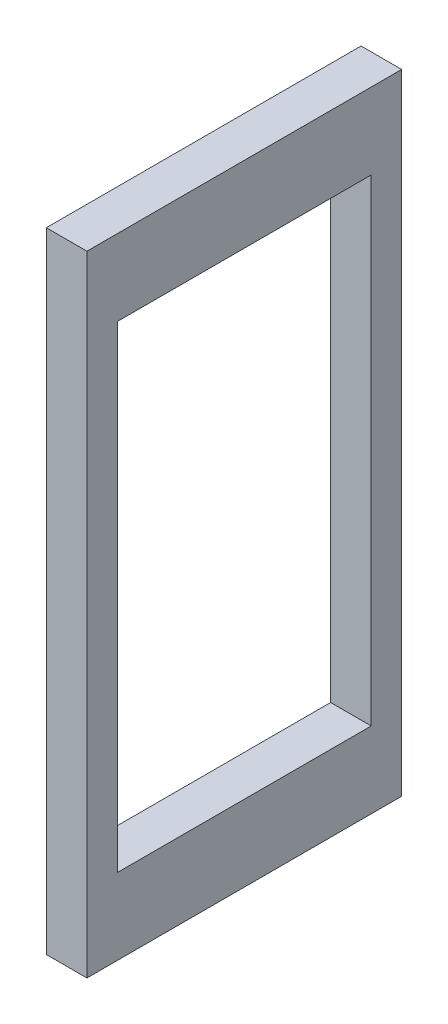
SolidWorks part; units mm, degrees
ref_plane "Front Plane" through (0, 0, 0) normal (1, 0, 0) x (0, 1, 0)
ref_plane "Top Plane" through (0, 0, 0) normal (0, 0, 1) x (0, 1, 0)
ref_plane "Right Plane" through (0, 0, 0) normal (0, 1, 0) x (-1, 0, 0)
sketch "Sketch1" plane through (0, 0, 0) normal (1, 0, 0) x (0, 1, 0)
  line L0 (-15.1573, 5.6511) -> (-15.1573, 7.1511)
  line L1 (12.0919, -6.8489) -> (-11.4081, -6.8489)
  line L2 (15.8412, -7.1519) -> (15.8412, 6.8481)
  line L3 (12.0919, 5.6511) -> (-11.4081, 5.6511)
  line L4 (-15.1573, -6.8489) -> (-15.1573, 5.6511)
  line L7 (12.0919, -6.8489) -> (-11.4081, -6.8489)
  line L8 (12.0919, -6.8489) -> (12.0919, 5.6511)
  line L9 (12.0919, 5.6511) -> (-11.4081, 5.6511)
  line L10 (-11.4081, -6.8489) -> (-11.4081, 5.6511)
  line L13 (-11.4081, 5.6511) -> (12.0919, 5.6511)
  line L14 (-15.1573, 7.1511) -> (15.8412, 7.1511)
  line L15 (15.8412, 6.8481) -> (15.8412, 7.1511)
  line L16 (-15.1573, -6.8489) -> (-15.1573, -8.3489)
  line L17 (-11.4081, -6.8489) -> (12.0919, -6.8489)
  line L18 (-15.1573, -8.3489) -> (15.8412, -8.3489)
  line L19 (15.8412, -7.1519) -> (15.8412, -8.3489)
  point P0 (0, 0)
  point P6 (0.3419, -0.1511)
  point P11 (0, 0)
  dimension "D1" = 31
  dimension "D2" = 12.5
  dimension "D3" = 23.5
  dimension "D4" = 1.5
  dimension "D5" = 1.5
extrude "Boss-Extrude1" add sketch "Sketch1" along normal blind 2 contours L19 L2 L15 L14 L0 L4 L16 L18 L1 L10 L3 L8
